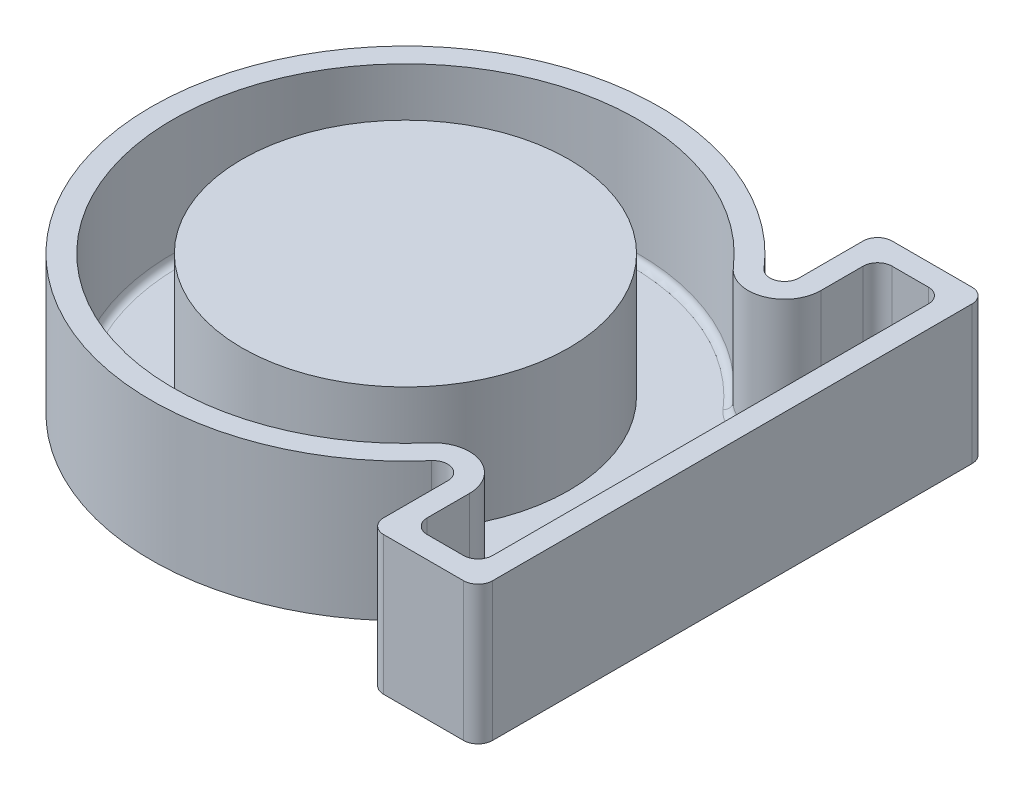
SolidWorks part; units mm, degrees
ref_plane "Alzado" through (0, 0, 0) normal (0, 0, 1) x (1, 0, 0)
ref_plane "Planta" through (0, 0, 0) normal (0, 1, 0) x (1, 0, 0)
ref_plane "Vista lateral" through (0, 0, 0) normal (1, 0, 0) x (0, 0, -1)
sketch "Sketch2" plane through (0, 0, 0) normal (0, 1, 0) x (1, 0, 0)
  line L0 (0, 0) -> (100, 0) construction
  line L1 (100, 0) -> (100, 100) construction
  line L2 (100, 100) -> (0, 100) construction
  line L3 (0, 100) -> (0, 0) construction
  line L4 (79.031, 24.0251) -> (79.031, 15.2119)
  line L5 (81.031, 83.2119) -> (92.031, 83.2119)
  line L6 (79.031, 81.2119) -> (79.031, 72.3987)
  line L7 (81.031, 13.2119) -> (92.031, 13.2119)
  line L8 (94.031, 81.2119) -> (94.031, 15.2119)
  arc A1 (75.5175, 71.0913) -> (75.5175, 25.3325) centre (49.031, 48.2119) ccw
  arc A2 (79.031, 15.2119) -> (81.031, 13.2119) centre (81.031, 15.2119) ccw
  arc A3 (92.031, 13.2119) -> (94.031, 15.2119) centre (92.031, 15.2119) ccw
  arc A4 (92.031, 83.2119) -> (94.031, 81.2119) centre (92.031, 81.2119) cw
  arc A5 (81.031, 83.2119) -> (79.031, 81.2119) centre (81.031, 81.2119) ccw
  arc A6 (79.031, 24.0251) -> (75.5175, 25.3325) centre (77.031, 24.0251) ccw
  arc A7 (79.031, 72.3987) -> (75.5175, 71.0913) centre (77.031, 72.3987) cw
  point P9 (84.031, 48.2119)
  point P22 (94.031, 13.2119)
  point P25 (94.031, 83.2119)
  point P28 (79.031, 83.2119)
  dimension "D5" = 70
  dimension "D8" = 2
  dimension "D1" = 100
  dimension "D2" = 100
  dimension "D3" = 100
  dimension "D4" = 100
  dimension "D6" = 70
  dimension "D7" = 15
extrude "Boss-Extrude1" add sketch "Sketch2" along normal blind 19.05
sketch "Sketch3" plane through (0, 19.05, 0) normal (0, 1, 0) x (1, 0, 0)
  line L10 (82.031, 16.2119) -> (91.031, 16.2119)
  line L11 (91.031, 16.2119) -> (91.031, 80.2119)
  line L12 (91.031, 80.2119) -> (82.031, 80.2119)
  line L13 (82.031, 80.2119) -> (82.031, 72.3987)
  line L14 (82.031, 24.0251) -> (82.031, 16.2119)
  line L15 (82.031, 16.2119) -> (91.031, 16.2119)
  line L16 (91.031, 16.2119) -> (91.031, 80.2119)
  line L17 (91.031, 80.2119) -> (82.031, 80.2119)
  line L18 (82.031, 80.2119) -> (82.031, 72.3987)
  line L19 (82.031, 24.0251) -> (82.031, 16.2119)
  circle A7 centre (49.031, 48.2119) radius 22.5
  arc A14 (73.2472, 69.1302) -> (82.031, 72.3987) centre (77.031, 72.3987) ccw
  arc A15 (73.2472, 69.1302) -> (73.2472, 27.2936) centre (49.031, 48.2119) ccw
  arc A16 (82.031, 24.0251) -> (73.2472, 27.2936) centre (77.031, 24.0251) ccw
  arc A17 (73.2472, 69.1302) -> (82.031, 72.3987) centre (77.031, 72.3987) ccw
  arc A18 (73.2472, 69.1302) -> (73.2472, 27.2936) centre (49.031, 48.2119) ccw
  arc A19 (82.031, 24.0251) -> (73.2472, 27.2936) centre (77.031, 24.0251) ccw
  dimension "D2" = 45
  dimension "D1" = 3
extrude "Cut-Extrude1" cut sketch "Sketch3" against normal blind 17
fillet "Fillet1" radius 2 4 edges at (91.031, 10.55, -16.2119) (82.031, 10.55, -16.2119) (91.031, 10.55, -80.2119) (82.031, 10.55, -80.2119)
fillet "Fillet2" radius 1 12 edges at (82.6168, 2.05, -16.7977) (82.031, 2.05, -21.1185) (78.7747, 2.05, -28.7112) (17.031, 2.05, -48.2119) (78.7747, 2.05, -67.7126) (82.031, 2.05, -75.3053) (82.6168, 2.05, -79.6261) (86.531, 2.05, -80.2119) (90.4452, 2.05, -79.6261) (91.031, 2.05, -48.2119) (90.4452, 2.05, -16.7977) (86.531, 2.05, -16.2119)
